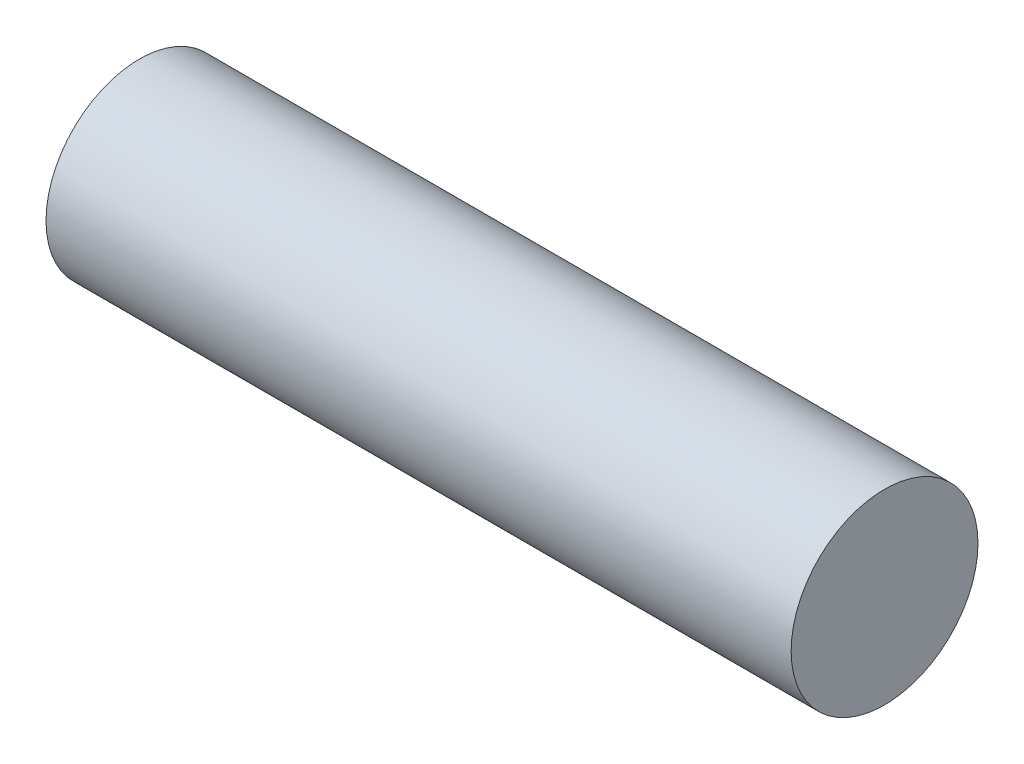
SolidWorks part; units mm, degrees
ref_plane "Front Plane" through (0, 0, 0) normal (1, 0, 0) x (0, 1, 0)
ref_plane "Top Plane" through (0, 0, 0) normal (0, 0, 1) x (0, 1, 0)
ref_plane "Right Plane" through (0, 0, 0) normal (0, 1, 0) x (-1, 0, 0)
sketch "Sketch2" plane through (0, 0, 0) normal (1, 0, 0) x (0, 1, 0)
  circle A0 centre (0, 0) radius 5
  dimension "D1" = 10
extrude "Boss-Extrude1" add sketch "Sketch2" along normal mid plane 39.878
